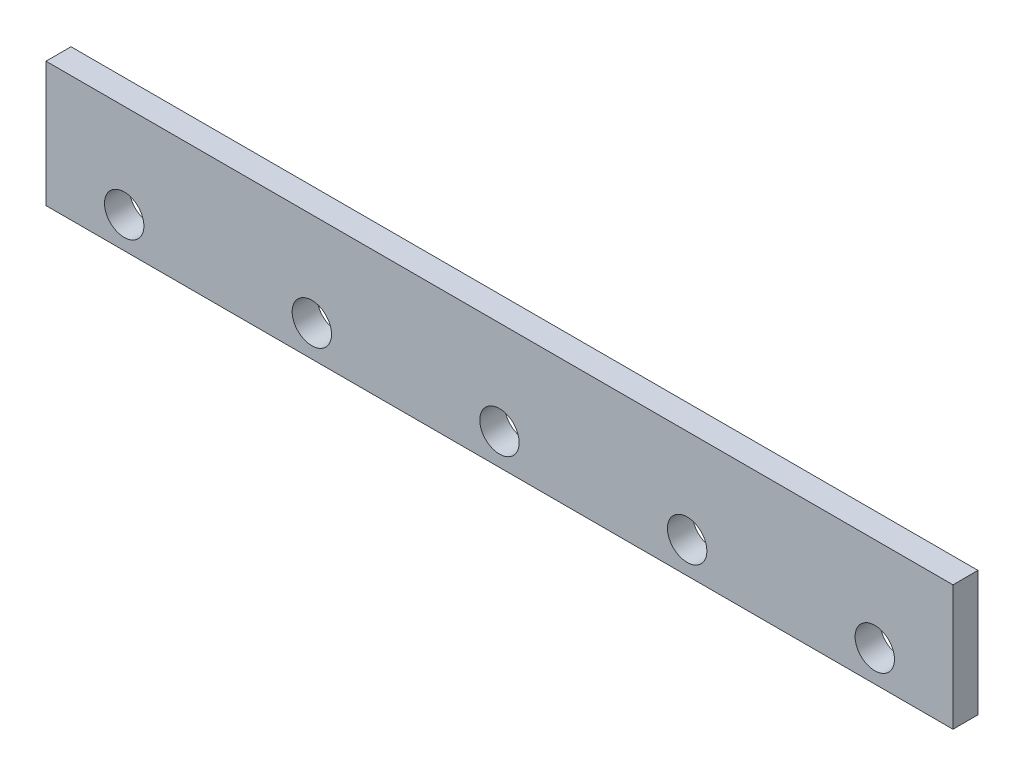
SolidWorks part; units mm, degrees
ref_plane "前基準面" through (0, 0, 0) normal (0, 0, 1) x (1, 0, 0)
ref_plane "上基準面" through (0, 0, 0) normal (0, 1, 0) x (1, 0, 0)
ref_plane "右基準面" through (0, 0, 0) normal (1, 0, 0) x (0, 0, -1)
sketch "草圖1" plane through (0, 0, 0) normal (0, 0, 1) x (1, 0, 0)
  line L0 (50, 20) -> (170, 20)
  line L1 (0, 0) -> (580, 0)
  line L2 (0, 0) -> (0, 80)
  line L3 (0, 80) -> (580, 80)
  line L4 (580, 0) -> (580, 80)
  line L5 (170, 20) -> (290, 20)
  line L6 (290, 20) -> (410, 20)
  line L7 (410, 20) -> (530, 20)
  circle A0 centre (50, 20) radius 12.6
  circle A1 centre (170, 20) radius 12.6
  circle A2 centre (290, 20) radius 12.6
  circle A3 centre (410, 20) radius 12.6
  circle A4 centre (530, 20) radius 12.6
  dimension "D9" = 25.2
  dimension "D10" = 25.2
  dimension "D11" = 25.2
  dimension "D12" = 25.2
  dimension "D13" = 25.2
  dimension "D1" = 80
  dimension "D2" = 580
  dimension "D3" = 120
  dimension "D4" = 120
  dimension "D5" = 120
  dimension "D6" = 120
  dimension "D7" = 50
  dimension "D8" = 20
extrude "填料-伸長1" add sketch "草圖1" along normal blind 16
